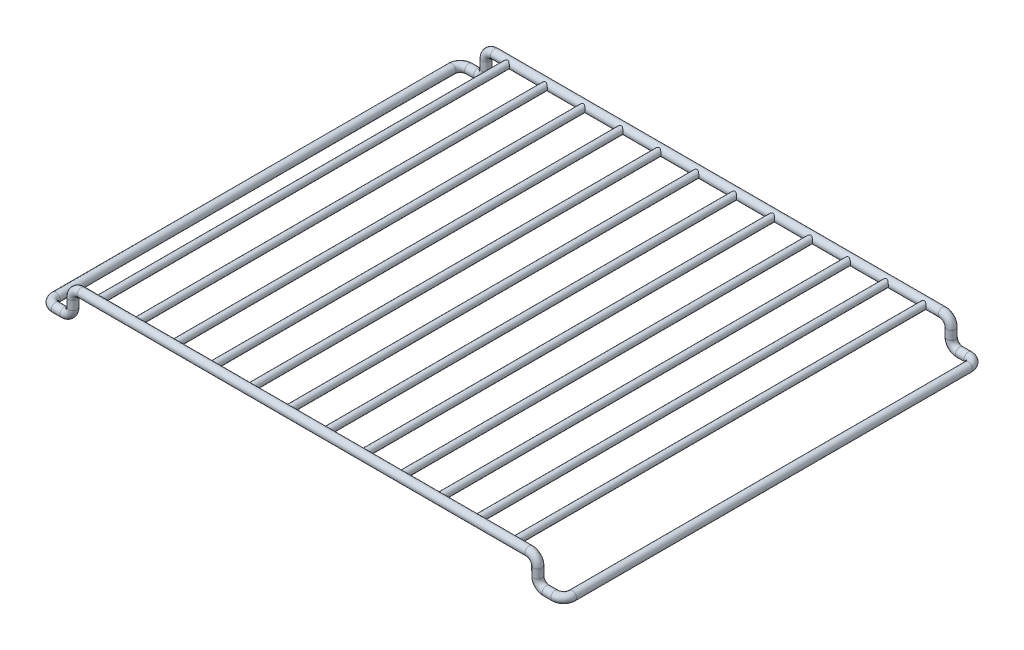
SolidWorks part; units mm, degrees
ref_plane "Front Plane" through (0, 0, 0) normal (0, 0, 1) x (1, 0, 0)
ref_plane "Top Plane" through (0, 0, 0) normal (0, 1, 0) x (1, 0, 0)
ref_plane "Right Plane" through (0, 0, 0) normal (1, 0, 0) x (0, 0, -1)
sketch3d "3DSketch1"
  line L0 (0, 0, 0) -> (130, 0, 0)
  line L1 (135, -5, 0) -> (135, -10, 0)
  line L2 (140, -15, 0) -> (145, -15, 0)
  line L3 (150, -15, 5) -> (150, -15, 235)
  line L4 (145, -15, 240) -> (140, -15, 240)
  line L5 (135, -10, 240) -> (135, -5, 240)
  line L6 (130, 0, 240) -> (0, 0, 240)
  arc A0 (130, 0, 0) -> (135, -5, 0) centre (130, -5, 0) ccw
  arc A1 (135, -10, 0) -> (140, -15, 0) centre (140, -10, 0) ccw
  arc A2 (145, -15, 0) -> (150, -15, 5) centre (145, -15, 5) ccw
  arc A3 (150, -15, 235) -> (145, -15, 240) centre (145, -15, 235) ccw
  arc A4 (140, -15, 240) -> (135, -10, 240) centre (140, -10, 240) ccw
  arc A5 (135, -5, 240) -> (130, 0, 240) centre (130, -5, 240) ccw
  point P12 (135, 0, 0)
  point P13 (130, -5, -5)
  point P16 (135, -15, 0)
  point P17 (140, -10, 5)
  point P20 (150, -15, 0)
  point P21 (145, -20, 5)
  point P24 (150, -15, 240)
  point P25 (145, -20, 235)
  point P28 (135, -15, 240)
  point P29 (140, -10, 235)
  point P32 (135, 0, 240)
  point P33 (130, -5, 245)
  dimension "D8" = 5
  dimension "D1" = 135
  dimension "D2" = 240
  dimension "D3" = 15
  dimension "D4" = 15
  dimension "D5" = 15
  dimension "D6" = 15
  dimension "D7" = 135
sketch "Sketch1" plane through (0, 0, 0) normal (1, 0, 0) x (0, 0, -1)
  circle A0 centre (0, 0) radius 2.5
  dimension "D1" = 5
sweep "Sweep1" add profiles "Sketch1" path "3DSketch1"
sketch "Sketch2" plane through (0, 0, 0) normal (0, 0, 1) x (1, 0, 0)
  circle A0 centre (11, 0) radius 2
  dimension "D1" = 4
  dimension "D2" = 11
extrude "Boss-Extrude1" add sketch "Sketch2" along normal up to surface (237.5 mm away)
pattern_linear "LPattern1" count 6 spacing 22 along (1, 0, 0) of "Boss-Extrude1"
mirror "Mirror1" about plane through (0, 0, 240) normal (-1, 0, 0) of bodies 103
